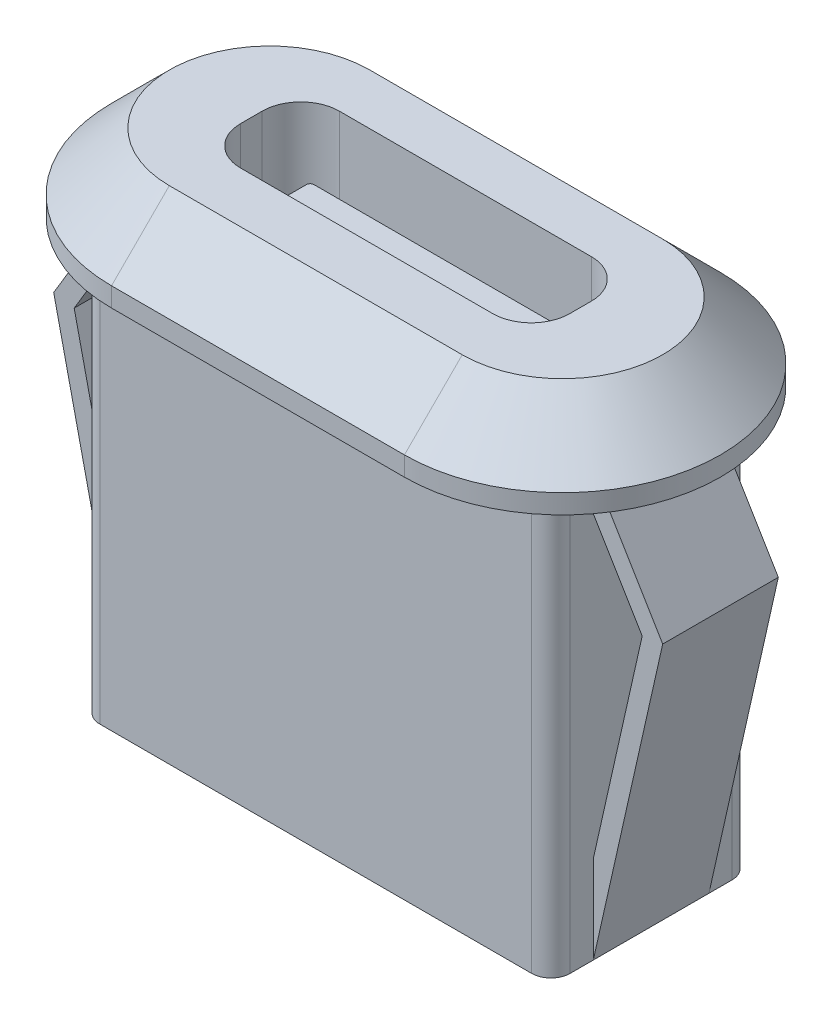
SolidWorks part; units mm, degrees
ref_plane "Alzado" through (0, 0, 0) normal (0, 0, 1) x (1, 0, 0)
ref_plane "Planta" through (0, 0, 0) normal (0, 1, 0) x (1, 0, 0)
ref_plane "Vista lateral" through (0, 0, 0) normal (1, 0, 0) x (0, 0, -1)
sketch "Croquis1" plane through (0, 0, 0) normal (0, 1, 0) x (1, 0, 0)
  line L1 (-5.6, -2.6) -> (5.6, -2.6)
  line L2 (-6.1, -2.1) -> (-6.1, 2.1)
  line L3 (-5.6, 2.6) -> (5.6, 2.6)
  line L4 (6.1, -2.1) -> (6.1, 2.1)
  line L5 (-6.1, -2.6) -> (6.1, 2.6) construction
  line L6 (-6.1, 2.6) -> (6.1, -2.6) construction
  arc A0 (6.1, 2.1) -> (5.6, 2.6) centre (5.6, 2.1) ccw
  arc A1 (5.6, -2.6) -> (6.1, -2.1) centre (5.6, -2.1) ccw
  arc A2 (-5.6, -2.6) -> (-6.1, -2.1) centre (-5.6, -2.1) cw
  arc A3 (-5.6, 2.6) -> (-6.1, 2.1) centre (-5.6, 2.1) ccw
  point P0 (0, 0)
  dimension "D3" = 0.5
  dimension "D1" = 12.2
  dimension "D2" = 5.2
extrude "Saliente-Extruir1" add sketch "Croquis1" against normal blind 11
sketch "Croquis2" plane through (0, 0, 0) normal (0, 1, 0) x (1, 0, 0)
  line L0 (-6.1, 2.1) -> (-6.1, -2.1) construction
  line L1 (-3.8, -4.1) -> (3.8, -4.1)
  line L2 (-7.9, -4.1) -> (-7.9, 4.1) construction
  line L3 (-3.8, 4.1) -> (3.8, 4.1)
  line L4 (7.9, -4.1) -> (7.9, 4.1) construction
  line L7 (5.6, 2.6) -> (-5.6, 2.6) construction
  arc A0 (-3.8, 4.1) -> (-3.8, -4.1) centre (-3.8, 0) ccw
  arc A1 (3.8, 4.1) -> (3.8, -4.1) centre (3.8, 0) cw
  point P0 (0, 0)
  dimension "D3" = 9.9
  dimension "D1" = 15.8
  dimension "D2" = 2.3
  dimension "D4" = 2.6
  dimension "D5" = 8.2
extrude "Saliente-Extruir2" add sketch "Croquis2" along normal blind 0.5
sketch "Croquis3" plane through (0, 0.5, 0) normal (0, 1, 0) x (1, 0, 0)
  line L0 (-3.8, -4.1) -> (3.8, -4.1)
  line L2 (-3.8, 4.1) -> (3.8, 4.1)
  line L3 (3.8, 0) -> (-3.8, 0) construction
  line L4 (-3.8, -4.1) -> (3.8, -4.1) construction
  line L5 (3.8, 4.1) -> (-3.8, 4.1) construction
  arc A0 (-3.8, 4.1) -> (-3.8, -4.1) centre (-3.8, 0) ccw
  arc A1 (3.8, 4.1) -> (3.8, -4.1) centre (3.8, 0) cw
  point P1 (-0.5334, -1.0786)
  point P2 (0, 0)
  dimension "D1" = 4.1
extrude "Saliente-Extruir3" add sketch "Croquis3" along normal blind 1.5 draft 45
sketch "Croquis6" plane through (0, 2, 0) normal (0, 1, 0) x (1, 0, 0)
  line L1 (-3.27, 1.28) -> (3.27, 1.28)
  line L2 (-4.27, 0.28) -> (-4.27, -0.28)
  line L3 (-3.27, -1.28) -> (3.27, -1.28)
  line L4 (4.27, 0.28) -> (4.27, -0.28)
  line L5 (-4.27, 1.28) -> (4.27, -1.28) construction
  line L6 (-4.27, -1.28) -> (4.27, 1.28) construction
  arc A0 (4.27, -0.28) -> (3.27, -1.28) centre (3.27, -0.28) cw
  arc A1 (-4.27, -0.28) -> (-3.27, -1.28) centre (-3.27, -0.28) ccw
  arc A2 (4.27, 0.28) -> (3.27, 1.28) centre (3.27, 0.28) ccw
  arc A3 (-3.27, 1.28) -> (-4.27, 0.28) centre (-3.27, 0.28) ccw
  point P0 (0, 0)
  dimension "D3" = 1
  dimension "D1" = 8.54
  dimension "D2" = 2.56
extrude "Cortar-Extruir1" cut sketch "Croquis6" against normal blind 6
sketch "Croquis7" plane through (0, -4, 0) normal (0, 1, 0) x (1, 0, 0)
  line L1 (-3.345, -0.6) -> (3.345, -0.6)
  line L2 (-3.345, -0.6) -> (-3.345, 0.6)
  line L3 (-3.345, 0.6) -> (3.345, 0.6)
  line L4 (3.345, -0.6) -> (3.345, 0.6)
  line L5 (-3.345, -0.6) -> (3.345, 0.6) construction
  line L6 (-3.345, 0.6) -> (3.345, -0.6) construction
  point P0 (0, 0)
  dimension "D1" = 1.2
  dimension "D2" = 6.69
extrude "Saliente-Extruir4" add sketch "Croquis7" along normal blind 4.7
fillet "Redondeo1" radius 0.1 4 edges at (3.345, -1.65, -0.6) (3.345, -1.65, 0.6) (-3.345, -1.65, -0.6) (-3.345, -1.65, 0.6)
sketch "Croquis8" plane through (0, 0, 0) normal (0, 0, 1) x (1, 0, 0)
  line L0 (-6.1, 0) -> (-7.9, -3)
  line L1 (-7.9, -3) -> (-6.1, -11)
  line L2 (-6.1, -11) -> (-6.1, -8.7222)
  line L3 (-6.1, -11) -> (-6.1, 0) construction
  line L4 (-6.1, -8.7222) -> (-7.3682, -3.0856)
  line L5 (-7.3682, -3.0856) -> (-6.1, -0.9718)
  line L6 (-6.1, -0.9718) -> (-6.1, 0)
  line L7 (0, 4.5087) -> (0, -14.2184) construction
  line L8 (-7.9, 0) -> (-3.8, 0) construction
  line L9 (-7.9, 0.5) -> (-7.9, 0) construction
  line L10 (-7.9, 0.25) -> (-7.9, -5.2597) construction
  line L11 (6.1, -0.9718) -> (6.1, 0)
  line L12 (7.3682, -3.0856) -> (6.1, -0.9718)
  line L13 (6.1, -8.7222) -> (7.3682, -3.0856)
  line L14 (6.1, -11) -> (6.1, -8.7222)
  line L15 (7.9, -3) -> (6.1, -11)
  line L16 (6.1, 0) -> (7.9, -3)
  point P15 (0, 0)
  point P20 (-7.3614, -2.9582)
  dimension "D1" = 3
  dimension "D2" = 0.5
  dimension "D3" = 0.5
extrude "Saliente-Extruir5" add sketch "Croquis8" along normal mid plane 3
